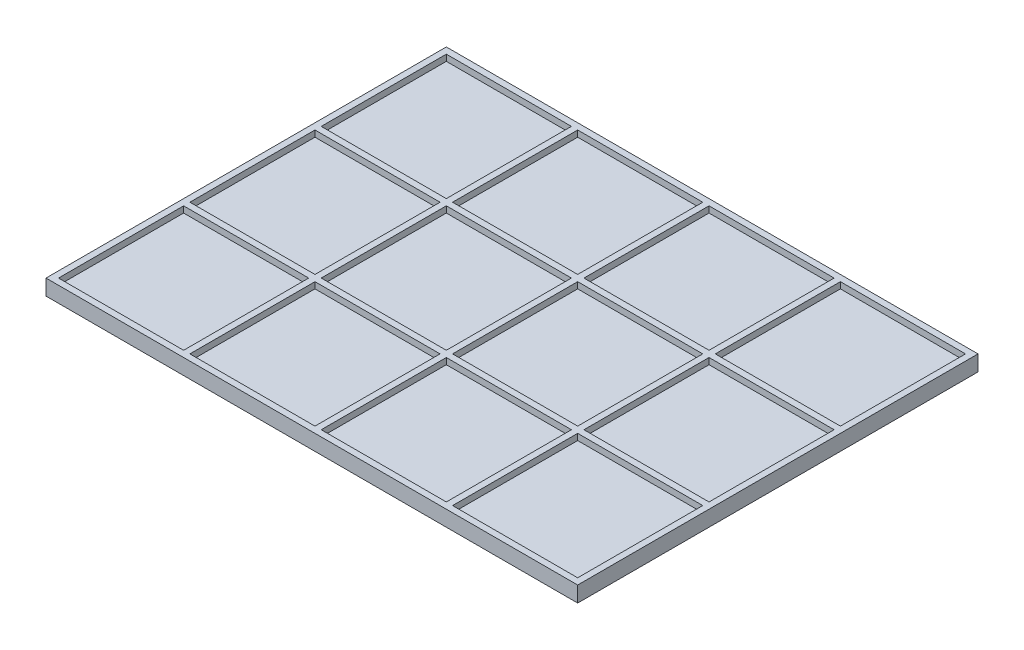
SolidWorks part; units mm, degrees
ref_plane "前视基准面" through (0, 0, 0) normal (0, 0, 1) x (1, 0, 0)
ref_plane "上视基准面" through (0, 0, 0) normal (0, 1, 0) x (1, 0, 0)
ref_plane "右视基准面" through (0, 0, 0) normal (1, 0, 0) x (0, 0, -1)
other "Configuration Table"
sketch "草图4" plane through (0, 0, 0) normal (0, 1, 0) x (1, 0, 0)
  line L0 (0, 0) -> (85, 0)
  line L1 (85, 0) -> (85, 64)
  line L2 (0, 0) -> (-85, 0)
  line L3 (-85, 0) -> (-85, -64)
  line L5 (-85, -64) -> (85, -64)
  line L6 (-85, -64) -> (-85, 64)
  line L7 (-85, 64) -> (85, 64)
  line L8 (85, -64) -> (85, 64)
extrude "凸台-拉伸1" add sketch "草图4" along normal blind 5 contours L7 L6 L2 L0 L1 | L5 L8 L0 L2 L3
sketch "草图5" plane through (0, 5, 0) normal (0, 1, 0) x (1, 0, 0)
  line L0 (-41, 62) -> (-41, 22)
  line L9 (-83, 62) -> (-43, 62)
  line L10 (-83, 62) -> (-83, 22)
  line L11 (-83, 22) -> (-43, 22)
  line L12 (-43, 62) -> (-43, 22)
  line L13 (-41, 62) -> (-1, 62)
  line L14 (-1, 62) -> (-1, 22)
  line L15 (-41, 22) -> (-1, 22)
  line L16 (1, 62) -> (1, 22)
  line L17 (1, 62) -> (41, 62)
  line L18 (41, 62) -> (41, 22)
  line L19 (1, 22) -> (41, 22)
  line L20 (43, 62) -> (43, 22)
  line L21 (43, 62) -> (83, 62)
  line L22 (83, 62) -> (83, 22)
  line L23 (43, 22) -> (83, 22)
  line L24 (-41, 20) -> (-41, -20)
  line L25 (-41, 20) -> (-1, 20)
  line L26 (-1, 20) -> (-1, -20)
  line L27 (-41, -20) -> (-1, -20)
  line L28 (1, 20) -> (1, -20)
  line L29 (1, 20) -> (41, 20)
  line L30 (41, 20) -> (41, -20)
  line L31 (1, -20) -> (41, -20)
  line L32 (43, 20) -> (43, -20)
  line L33 (43, 20) -> (83, 20)
  line L34 (83, 20) -> (83, -20)
  line L35 (43, -20) -> (83, -20)
  line L36 (-41, -22) -> (-41, -62)
  line L37 (-41, -22) -> (-1, -22)
  line L38 (-1, -22) -> (-1, -62)
  line L39 (-41, -62) -> (-1, -62)
  line L40 (1, -22) -> (1, -62)
  line L41 (1, -22) -> (41, -22)
  line L42 (41, -22) -> (41, -62)
  line L43 (1, -62) -> (41, -62)
  line L44 (43, -22) -> (43, -62)
  line L45 (43, -22) -> (83, -22)
  line L46 (83, -22) -> (83, -62)
  line L47 (43, -62) -> (83, -62)
  line L48 (-83, 20) -> (-83, -20)
  line L49 (-83, 20) -> (-43, 20)
  line L50 (-43, 20) -> (-43, -20)
  line L51 (-83, -20) -> (-43, -20)
  line L52 (-83, -22) -> (-83, -62)
  line L53 (-83, -22) -> (-43, -22)
  line L54 (-43, -22) -> (-43, -62)
  line L55 (-83, -62) -> (-43, -62)
  dimension "D1" = 4
  dimension "D2" = 3
extrude "切除-拉伸1" cut sketch "草图5" against normal blind 2
sketch "草图7" plane through (0, 0, 0) normal (0, -1, 0) x (1, 0, 0)
  line L0 (0, 0) -> (50, 0)
  line L1 (50, 0) -> (50, 40)
  line L2 (0, 0) -> (-50, 0)
  line L3 (-50, 0) -> (-50, -40)
  line L4 (-50, 0) -> (-50, 40)
  line L5 (50, 0) -> (50, -40)
  circle A0 centre (-50, 40) radius 2.5
  circle A1 centre (50, 40) radius 2.5
  circle A2 centre (50, -40) radius 2.5
  circle A3 centre (-50, -40) radius 2.5
extrude "切除-拉伸2" cut sketch "草图7" against normal blind 1.6
sketch "草图8" plane through (0, 0, 0) normal (0, -1, 0) x (1, 0, 0)
  circle A0 centre (-50, 40) radius 2.6
  circle A1 centre (50, 40) radius 2.6
  circle A2 centre (50, -40) radius 2.6
  circle A3 centre (-50, -40) radius 2.6
extrude "切除-拉伸3" cut sketch "草图8" against normal blind 1.6
sketch "草图9" plane through (0, 0, 0) normal (0, -1, 0) x (1, 0, 0)
  circle A0 centre (-50, 40) radius 5.1
  circle A1 centre (50, 40) radius 5.1
  circle A2 centre (50, -40) radius 5.1
  circle A3 centre (-50, -40) radius 5.1
extrude "切除-拉伸4" cut sketch "草图9" against normal blind 1.6
